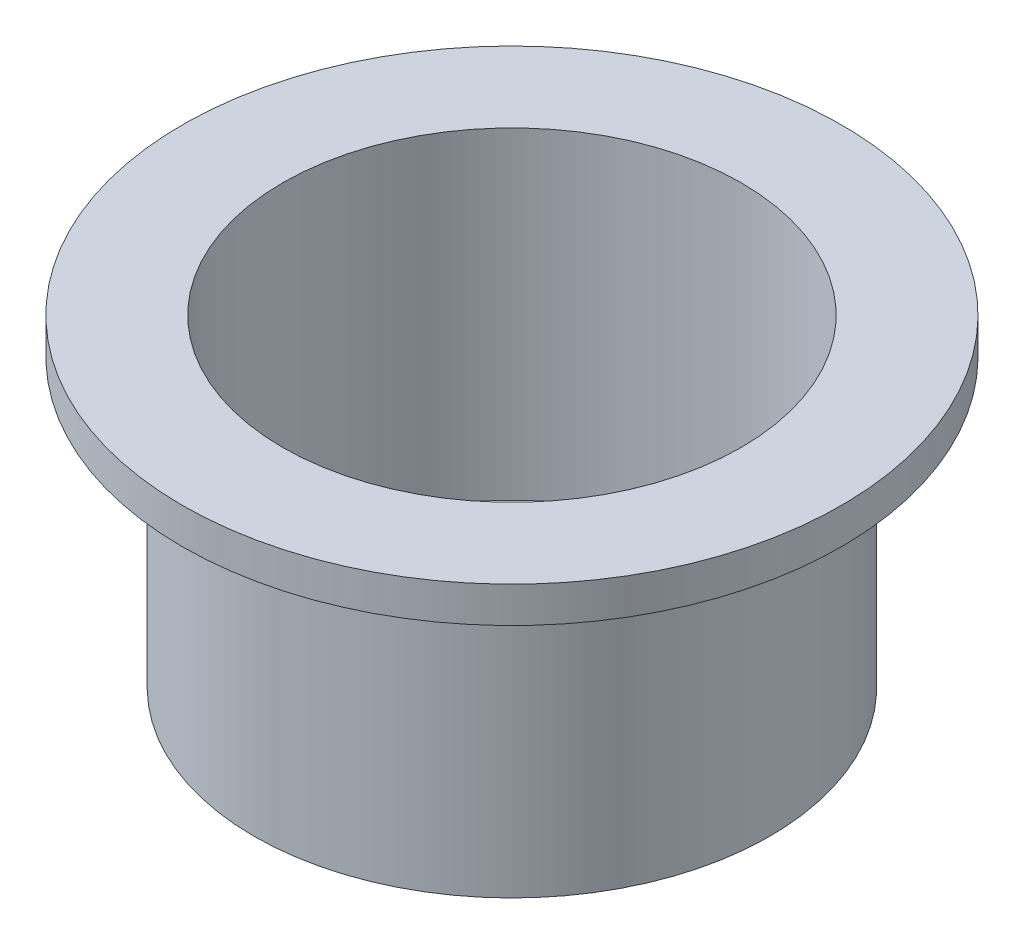
SolidWorks part; units mm, degrees
ref_plane "Front Plane" through (0, 0, 0) normal (0, 0, 1) x (1, 0, 0)
ref_plane "Top Plane" through (0, 0, 0) normal (0, 1, 0) x (1, 0, 0)
ref_plane "Right Plane" through (0, 0, 0) normal (1, 0, 0) x (0, 0, -1)
sketch "Sketch1" plane through (0, 0, 0) normal (0, 1, 0) x (1, 0, 0)
  circle A0 centre (0, 0) radius 11.43
  circle A2 centre (0, 0) radius 10.16
  dimension "D1" = 22.86
  dimension "D3" = 20.32
extrude "Boss-Extrude1" add sketch "Sketch1" along normal blind 12.7
sketch "Sketch2" plane through (0, 12.7, 0) normal (0, 1, 0) x (1, 0, 0)
  circle A0 centre (0, 0) radius 14.605
  circle A1 centre (0, 0) radius 10.16
  dimension "D1" = 29.21
extrude "Boss-Extrude2" add sketch "Sketch2" along normal blind 1.5875
